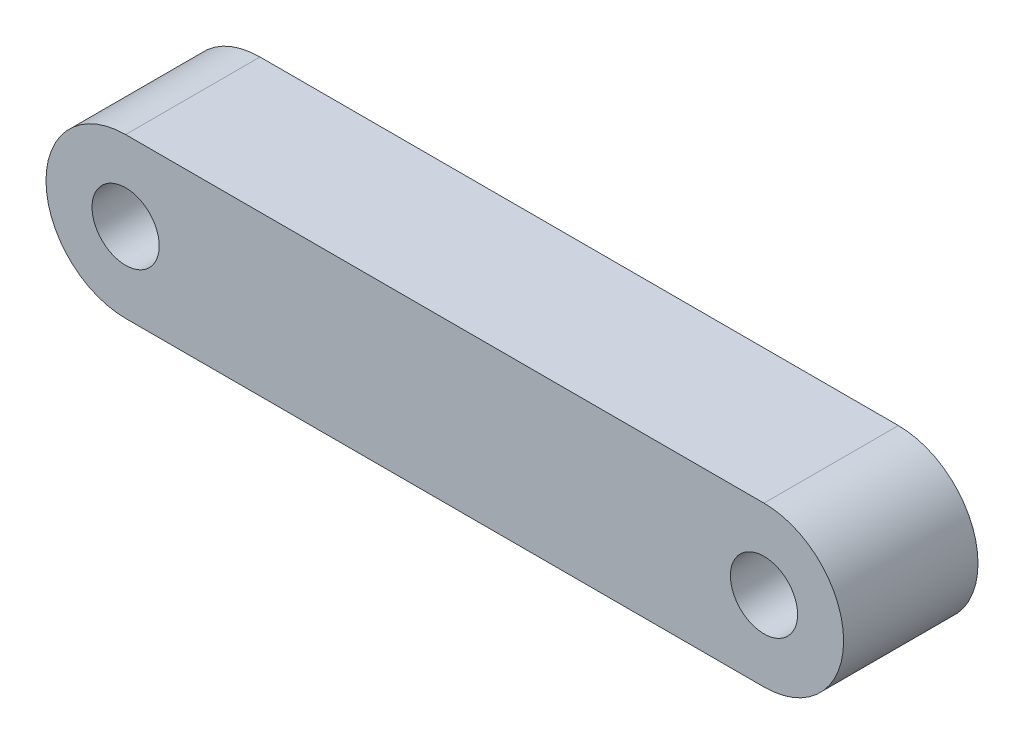
SolidWorks part; units mm, degrees
ref_plane "Front Plane" through (0, 0, 0) normal (0, 0, 1) x (1, 0, 0)
ref_plane "Top Plane" through (0, 0, 0) normal (0, 1, 0) x (1, 0, 0)
ref_plane "Right Plane" through (0, 0, 0) normal (1, 0, 0) x (0, 0, -1)
sketch "Sketch1" plane through (0, 0, 0) normal (0, 0, 1) x (1, 0, 0)
  line L0 (-9.0735, 0) -> (9.9265, 0) construction
  line L1 (-9.0735, 2.37) -> (9.9265, 2.37)
  line L2 (-9.0735, -2.37) -> (9.9265, -2.37)
  arc A0 (-9.0735, 2.37) -> (-9.0735, -2.37) centre (-9.0735, 0) ccw
  arc A1 (9.9265, -2.37) -> (9.9265, 2.37) centre (9.9265, 0) ccw
  circle A2 centre (9.9265, 0) radius 1
  circle A3 centre (-9.0735, 0) radius 1
  point P3 (0.4265, 0)
  dimension "D2" = 2.37
  dimension "D3" = 2
  dimension "D1" = 19
extrude "Boss-Extrude1" add sketch "Sketch1" along normal blind 4
